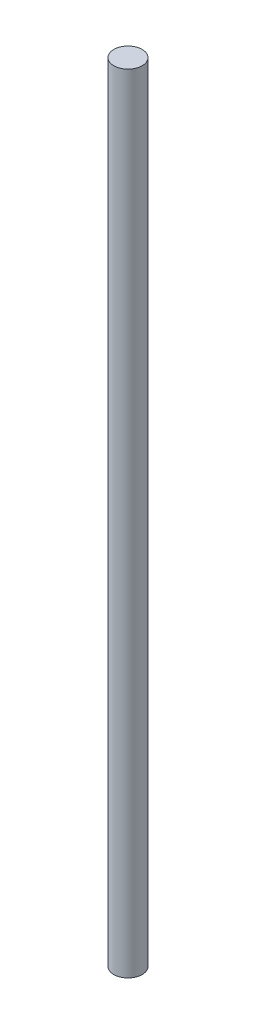
SolidWorks part; units mm, degrees
ref_plane "Front Plane" through (0, 0, 0) normal (0, 0, 1) x (1, 0, 0)
ref_plane "Top Plane" through (0, 0, 0) normal (0, 1, 0) x (1, 0, 0)
ref_plane "Right Plane" through (0, 0, 0) normal (1, 0, 0) x (0, 0, -1)
sketch "Sketch2" plane through (0, 0, 0) normal (0, 1, 0) x (1, 0, 0)
  circle A0 centre (0, 0) radius 2.25
  dimension "D1" = 4.5
extrude "Boss-Extrude1" add sketch "Sketch2" along normal mid plane 125
